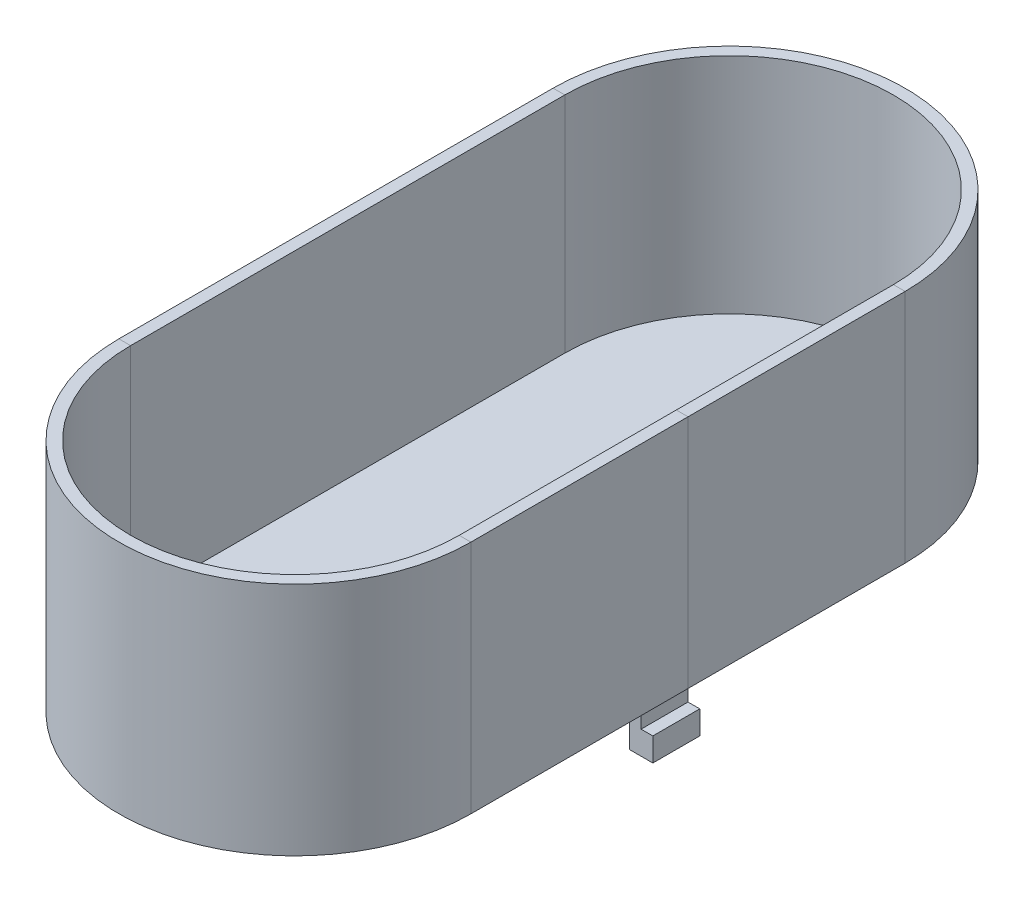
SolidWorks part; units mm, degrees
ref_plane "Front Plane" through (0, 0, 0) normal (0, 0, 1) x (1, 0, 0)
ref_plane "Top Plane" through (0, 0, 0) normal (0, 1, 0) x (1, 0, 0)
ref_plane "Right Plane" through (0, 0, 0) normal (1, 0, 0) x (0, 0, -1)
sketch "Sketch1" plane through (0, 0, 0) normal (0, 0, 1) x (1, 0, 0)
  line L1 (15.5, 10.0532) -> (15.5, -10)
  line L7 (16.5, 10.0532) -> (16.5, -10)
  line L8 (-10.67, 12.9449) -> (-10.67, 11) construction
  line L10 (1.5, -1.4558) -> (1.5, 1.8119) construction
  line L15 (1.5, -1.4558) -> (1.5, -12.7223) construction
  line L16 (1.5, -10) -> (1.5, -11)
  line L17 (15.5, -10) -> (16.5, -10)
  line L18 (15.5, 10.0532) -> (16.5, 10.0532)
  point P0 (15.5, 10.0532)
  dimension "D2" = 14
  dimension "D3" = 1
  dimension "D8" = 1.5
sketch "Sketch2" plane through (0, 0, 0) normal (0, 1, 0) x (1, 0, 0)
  line L0 (15.5, -18.5) -> (15.5, 18.5)
  line L1 (1.5, 32.5) -> (1.5, -32.5) construction
  line L2 (-12.5, -18.5) -> (-12.5, 18.5)
  line L4 (1.5, 0) -> (16.5, 0) construction
  arc A0 (15.5, 18.5) -> (-12.5, 18.5) centre (1.5, 18.5) ccw
  arc A1 (-12.5, -18.5) -> (15.5, -18.5) centre (1.5, -18.5) ccw
  dimension "D3" = 14
  dimension "D1" = 28
  dimension "D2" = 0
  dimension "D5" = 37
sweep "Sweep9" add profiles "Sketch1" path "Sketch2"
sketch "Sketch6" plane through (0, -10, 0) normal (0, -1, 0) x (1, 0, 0)
  line L0 (15.5, 0) -> (15.5, -18.5) construction
  line L1 (15.5, 18.5) -> (15.5, 0) construction
  line L2 (-12.5, -18.5) -> (-12.5, 18.5) construction
  line L3 (15.5, 0) -> (15.5, -18.5)
  line L4 (15.5, 18.5) -> (15.5, 0)
  line L5 (-12.5, -18.5) -> (-12.5, 18.5)
  arc A0 (-12.5, -18.5) -> (15.5, -18.5) centre (1.5, -18.5) ccw construction
  arc A1 (15.5, 18.5) -> (-12.5, 18.5) centre (1.5, 18.5) ccw construction
  arc A2 (-12.5, -18.5) -> (15.5, -18.5) centre (1.5, -18.5) ccw
  arc A3 (15.5, 18.5) -> (-12.5, 18.5) centre (1.5, 18.5) ccw
extrude "Boss-Extrude2" add sketch "Sketch6" against normal blind 1
sketch "Sketch7" plane through (0, 0, 0) normal (0, 0, 1) x (1, 0, 0)
  line L12 (0, 3.194) -> (0, -3.7946) construction
sketch "Sketch8" plane through (0, 0, 0) normal (0, 0, 1) x (1, 0, 0)
  line L4 (1.5, -9.2043) -> (1.5, -11.6364) construction
  line L5 (-12.5, -15) -> (-12.5, -13)
  line L6 (-11.5, -10) -> (-10.5, -10)
  line L7 (-12.5, -15) -> (-10.5, -15)
  line L12 (-10.5, -13) -> (-10.5, -15)
  line L13 (-12.5, -13) -> (-11.5, -13)
  line L15 (-10.5, -13) -> (-10.5, -10)
  line L22 (-11.5, -13) -> (-11.5, -10)
  line L29 (16.5, 10.0532) -> (-13.5, 10.0532) construction
  line L32 (14.5, -13) -> (14.5, -10)
  line L33 (13.5, -13) -> (13.5, -10)
  line L34 (15.5, -13) -> (14.5, -13)
  line L35 (13.5, -13) -> (13.5, -15)
  line L36 (15.5, -15) -> (13.5, -15)
  line L37 (14.5, -10) -> (13.5, -10)
  line L38 (15.5, -15) -> (15.5, -13)
  point P24 (1.5, 10.0532)
  dimension "D1" = 2
  dimension "D2" = 3
  dimension "D3" = 2
  dimension "D5" = 28
extrude "Boss-Extrude4" add sketch "Sketch8" along normal mid plane 4
